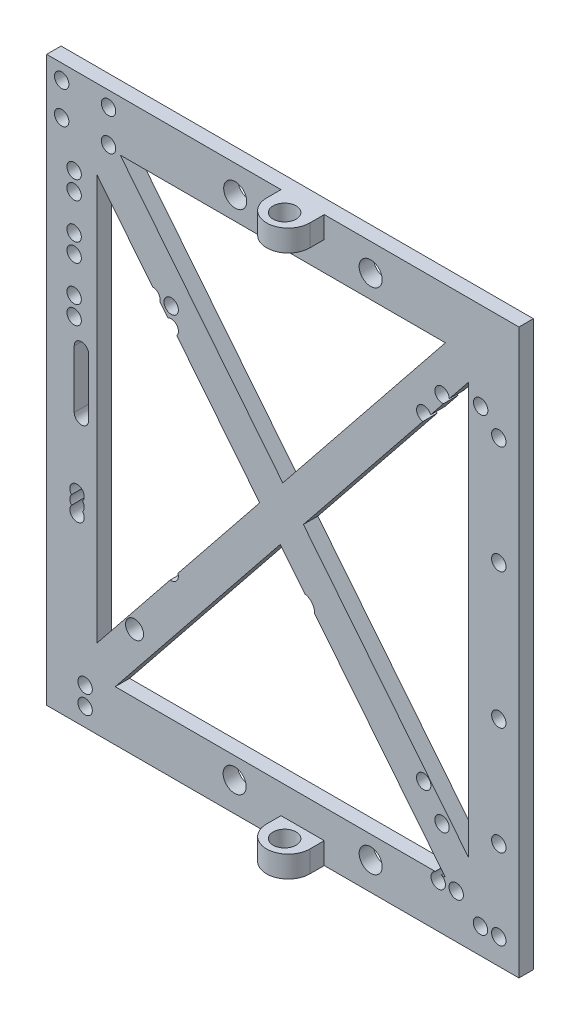
SolidWorks part; units mm, degrees
ref_plane "Front Plane" through (0, 0, 0) normal (0, 0, 1) x (1, 0, 0)
ref_plane "Top Plane" through (0, 0, 0) normal (0, 1, 0) x (1, 0, 0)
ref_plane "Right Plane" through (0, 0, 0) normal (1, 0, 0) x (0, 0, -1)
sketch "Sketch3" plane through (0, 0, 0) normal (0, 0, 1) x (1, 0, 0)
  line L0 (-58.532, 67.237) -> (-58.532, 10.995)
  line L1 (-65.532, 78.232) -> (0, 78.232)
  line L2 (-65.532, 78.232) -> (-65.532, 0)
  line L3 (-65.532, 0) -> (0, 0)
  line L4 (0, 78.232) -> (0, 0)
  line L5 (-56.0191, 7) -> (-10.2051, 7)
  line L6 (-7, 68.0998) -> (-7, 10.995)
  line L8 (-59.706, 45.116) -> (-59.706, 37.116)
  line L9 (-58.532, 71.232) -> (-7, 7) construction
  line L10 (-7, 71.232) -> (-58.532, 7) construction
  line L11 (-55.3269, 71.232) -> (-32.766, 43.111)
  line L12 (-58.532, 67.237) -> (-35.9711, 39.116)
  line L13 (-56.0191, 7) -> (-33.1121, 35.5524)
  line L14 (-58.532, 10.995) -> (-35.9711, 39.116)
  line L15 (-58.532, 71.232) -> (-58.532, 7) construction
  line L16 (-58.532, 7) -> (-7, 7) construction
  line L17 (-33.1121, 35.5524) -> (-10.2051, 7)
  line L18 (-32.766, 43.111) -> (-10.2051, 71.232)
  line L19 (-29.907, 39.5474) -> (-7, 10.995)
  line L20 (-29.907, 39.5474) -> (-7, 68.0998)
  line L21 (-58.532, 71.232) -> (-7, 71.232) construction
  line L22 (-55.3269, 71.232) -> (-10.2051, 71.232)
  line L23 (-7, 71.232) -> (-7, 7) construction
  line L25 (-61.706, 37.116) -> (-61.706, 45.116)
  circle A0 centre (-61.722, 66.169) radius 1
  circle A1 centre (-61.722, 63.629) radius 1
  circle A2 centre (-61.722, 58.669) radius 1
  circle A3 centre (-61.722, 56.129) radius 1
  circle A4 centre (-61.722, 51.169) radius 1
  circle A6 centre (-63.448, 76.164) radius 1
  circle A7 centre (-63.448, 71.664) radius 1
  circle A8 centre (-56.948, 71.664) radius 1
  circle A9 centre (-56.948, 76.164) radius 1
  circle A10 centre (-39.37, 74.422) radius 1.6
  circle A11 centre (-20.574, 74.422) radius 1.6
  circle A12 centre (-5.3091, 66.04) radius 1
  circle A13 centre (-2.794, 63.504) radius 1
  circle A14 centre (-2.794, 48.514) radius 1
  circle A15 centre (-2.794, 29.718) radius 1
  circle A16 centre (-2.794, 14.728) radius 1
  circle A17 centre (-2.799, 3.556) radius 1
  circle A18 centre (-5.339, 3.556) radius 1
  circle A19 centre (-8.7009, 6.096) radius 1
  circle A20 centre (-11.2009, 6.096) radius 1
  circle A21 centre (-20.574, 3.8909) radius 1.6
  circle A22 centre (-39.4509, 4.064) radius 1.6
  circle A23 centre (-60.198, 5.075) radius 1
  circle A24 centre (-60.198, 2.535) radius 1
  circle A25 centre (-61.32, 25.146) radius 1
  circle A26 centre (-61.32, 26.416) radius 1
  circle A27 centre (-61.32, 27.686) radius 1
  arc A28 (-61.706, 37.116) -> (-59.706, 37.116) centre (-60.706, 37.116) ccw
  arc A32 (-59.706, 45.116) -> (-61.706, 45.116) centre (-60.706, 45.116) ccw
  circle A33 centre (-61.722, 48.629) radius 1
  circle A34 centre (-48.255, 56.627) radius 1
  circle A35 centre (-13.213, 17.018) radius 1
  circle A36 centre (-10.668, 13.208) radius 1
  circle A37 centre (-48.26, 24.628) radius 1
  arc A39 (-47.4775, 53.4581) -> (-48.7004, 54.9823) centre (-48.255, 54.087) ccw
  arc A40 (-49.825, 56.3841) -> (-50.8218, 57.6266) centre (-50.795, 56.627) ccw
  circle A41 centre (-13.203, 61.214) radius 1
  circle A42 centre (-10.668, 64.77) radius 1
  circle A43 centre (-29.959, 29.718) radius 1.6
  circle A44 centre (-53.34, 15.24) radius 1.25
  dimension "D2" = 2
  dimension "D3" = 3.2
  dimension "D8" = 2.5
  dimension "D9" = 2
  dimension "D1" = 7
  dimension "D4" = 2.5
  dimension "D5" = 2.5
  dimension "D6" = 2.5
  dimension "D7" = 18.8769
extrude "Boss-Extrude10" add sketch "Sketch3" along normal blind 2 contours L4 L1 L2 L3 A44 A43 L17 L5 A20 L13 A42 L20 L6 L19 A41 A40 L12 A39 L14 A37 L0 A36 A35 A34 A33 A32 L8 A28 L25 A27 A26 A25
sketch3d "3DSketch1"
  line L0 (0, 0, 2) -> (0, 0, 0) construction
  line L2 (-20.574, 0, 0) -> (-20.574, 0, 2)
  line L3 (-65.532, 0, 0) -> (0, 0, 0) construction
  line L4 (-65.532, 0, 2) -> (0, 0, 2) construction
  dimension "D1" = 20.574
ref_plane "Plane1" through (0, 39.116, 0) normal (0, 1, 0) x (1, 0, 0)
sketch "Sketch5" plane through (0, 0, 0) normal (0, -1, 0) x (1, 0, 0)
  line L0 (-20.574, 2) -> (-20.574, 0)
  line L1 (-39.454, 2) -> (-39.454, 0)
  line L2 (-65.532, 2) -> (0, 2) construction
  line L3 (55, 0) -> (-55, 0) construction
  line L4 (-39.454, 1) -> (-20.574, 1) construction
  line L11 (-33.014, 2) -> (-27.014, 2)
  line L12 (-30.014, 2) -> (-30.014, 7) construction
  line L13 (-27.014, 2) -> (-27.014, 4)
  line L14 (-33.014, 2) -> (-33.014, 4)
  line L15 (-27.014, 2) -> (-27.014, 4)
  line L16 (-33.014, 2) -> (-33.014, 4)
  arc A2 (-33.014, 4) -> (-27.014, 4) centre (-30.014, 4) cw
  circle A3 centre (-30.014, 4.5) radius 1.6
  dimension "D1" = 18.88
extrude "Boss-Extrude11" add sketch "Sketch5" against normal blind 3
mirror "Mirror1" about plane through (0, 39.116, 0) normal (0, 1, 0) of "Boss-Extrude11"
